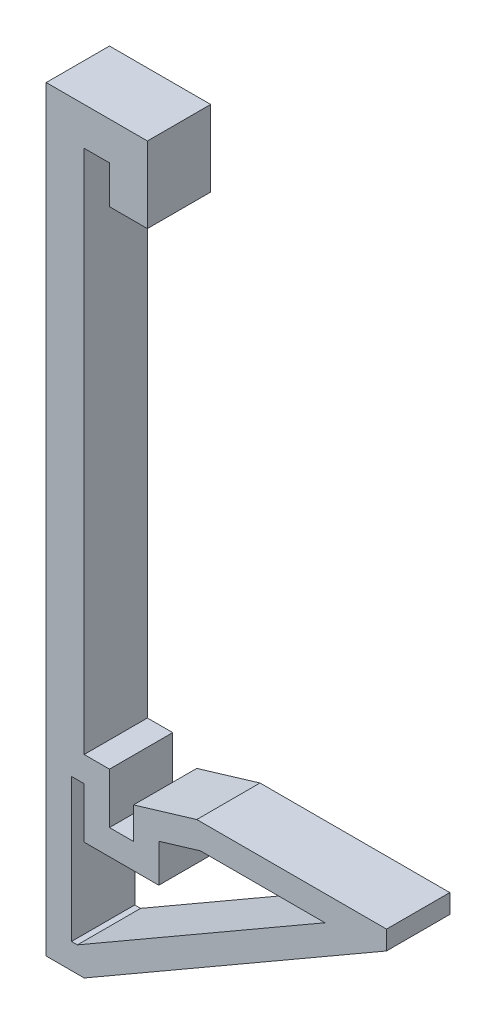
SolidWorks part; units mm, degrees
ref_plane "前视基准面" through (0, 0, 0) normal (0, 0, 1) x (1, 0, 0)
ref_plane "上视基准面" through (0, 0, 0) normal (0, 1, 0) x (1, 0, 0)
ref_plane "右视基准面" through (0, 0, 0) normal (1, 0, 0) x (0, 0, -1)
other "Configuration Table"
sketch "草图1" plane through (0, 0, 0) normal (0, 0, 1) x (1, 0, 0)
  line L0 (0, 0) -> (0, 59.7987)
  line L1 (0, 59.7987) -> (8, 59.7987)
  line L2 (8, 59.7987) -> (8, 53.7987)
  line L3 (8, 53.7987) -> (5, 53.7987)
  line L4 (5, 53.7987) -> (5, 56.7987)
  line L5 (5, 56.7987) -> (3, 56.7987)
  line L6 (3, 56.7987) -> (3, 15.2987)
  line L13 (3, 0) -> (26.9, 13.7987)
  line L14 (26.9, 13.7987) -> (6.9, 13.7987) construction
  line L15 (6.9, 13.7987) -> (6.9, 11.2987)
  line L16 (6.9, 11.2987) -> (5, 11.2987)
  line L17 (5, 11.2987) -> (5, 15.2987)
  line L18 (5, 15.2987) -> (3, 15.2987)
  line L19 (0, 0) -> (3, 0)
  line L20 (3, 15.2987) -> (0, 15.2987) construction
  line L21 (3, 56.7987) -> (0, 56.7987) construction
  line L22 (26.9, 15.2987) -> (11.9, 15.2987)
  line L23 (26.9, 15.2987) -> (26.9, 13.7987)
  line L24 (11.9, 15.2987) -> (6.9, 13.7987)
  dimension "D1" = 3
  dimension "D2" = 3
  dimension "D3" = 3
  dimension "D4" = 1.9
  dimension "D5" = 2
  dimension "D6" = 3
  dimension "D7" = 2.5
  dimension "D8" = 4
  dimension "D9" = 2
  dimension "D10" = 20
  dimension "D11" = 60
  dimension "D12" = 41.5
  dimension "D13" = 1.5
  dimension "D14" = 15
extrude "凸台-拉伸1" add sketch "草图1" along normal blind 5
sketch "草图2" plane through (0, 0, 5) normal (0, 0, 1) x (1, 0, 0)
  line L16 (22.034, 13.2987) -> (12.1935, 13.2987)
  line L17 (22.034, 13.2987) -> (12.1935, 13.2987)
  line L18 (12.1935, 13.2987) -> (8.9, 12.3106)
  line L19 (12.1935, 13.2987) -> (8.9, 12.3106)
  line L28 (2, 2) -> (2.4641, 2)
  line L29 (2.4641, 2) -> (22.034, 13.2987)
  line L31 (8.9, 12.3106) -> (8.9, 9.2987)
  line L32 (8.9, 9.2987) -> (3, 9.2987)
  line L33 (3, 9.2987) -> (3, 13.2987)
  line L34 (3, 13.2987) -> (2, 13.2987)
  line L35 (2, 13.2987) -> (2, 2)
  line L36 (2, 2) -> (2.4641, 2)
  line L37 (2.4641, 2) -> (22.034, 13.2987)
  line L39 (8.9, 12.3106) -> (8.9, 9.2987)
  line L40 (8.9, 9.2987) -> (3, 9.2987)
  line L41 (3, 9.2987) -> (3, 13.2987)
  line L42 (3, 13.2987) -> (2, 13.2987)
  line L43 (2, 13.2987) -> (2, 2)
  point P0 (0, 0)
  dimension "D1" = 2
extrude "切除-拉伸1" cut sketch "草图2" against normal through all
